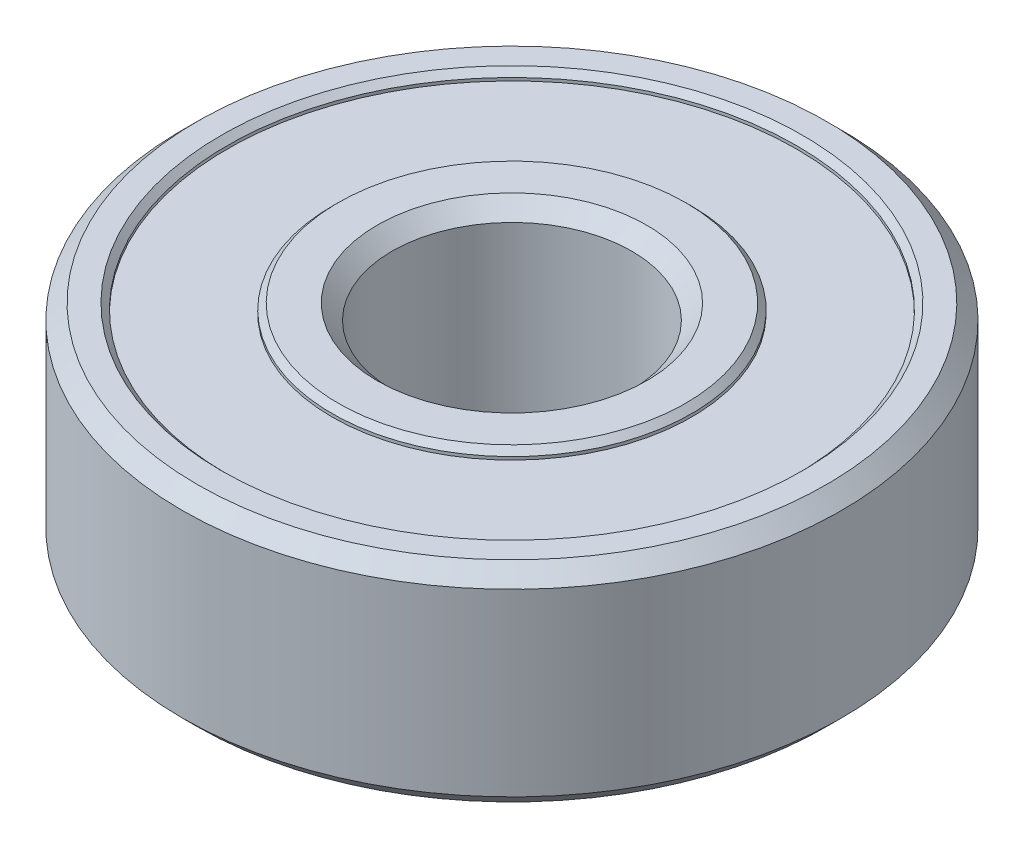
SolidWorks part; units mm, degrees
ref_plane "Front Plane" through (0, 0, 0) normal (0, 0, 1) x (1, 0, 0)
ref_plane "Top Plane" through (0, 0, 0) normal (0, 1, 0) x (1, 0, 0)
ref_plane "Right Plane" through (0, 0, 0) normal (1, 0, 0) x (0, 0, -1)
sketch "Sketch1" plane through (0, 0, 0) normal (0, 1, 0) x (1, 0, 0)
  circle A0 centre (0, 0) radius 11
  circle A1 centre (0, 0) radius 4
  circle A2 centre (0, 0) radius 6
  circle A3 centre (0, 0) radius 9.5
  dimension "D1" = 22
  dimension "D2" = 8
  dimension "D3" = 12
  dimension "D4" = 19
extrude "Boss-Extrude1" add sketch "Sketch1" along normal blind 7 contours A0 A3 | A2 A1
ref_plane "Plane1" through (0, 6.7, 0) normal (0, 1, 0) x (1, 0, 0)
ref_plane "Plane2" through (0, 0.3, 0) normal (0, -1, 0) x (-1, 0, 0)
sketch "Sketch2" plane through (0, 6.7, 0) normal (0, 1, 0) x (1, 0, 0)
  circle A2 centre (0, 0) radius 6
  circle A3 centre (0, 0) radius 6
  circle A5 centre (0, 0) radius 9.5
  circle A6 centre (0, 0) radius 9.5
  dimension "D1" = 0
  dimension "D2" = 0
extrude "Boss-Extrude2" add sketch "Sketch2" against normal up to surface (6.4 mm away) up to plane "Plane2"
chamfer "Chamfer1" distance 0.2 angle 45 4 edges at (0, 0, 6) (0, 0, 9.5) (0, 7, 9.5) (0, 7, 6)
chamfer "Chamfer2" distance 0.5 angle 45 4 edges at (0, 0, 11) (0, 7, 11) (0, 0, 4) (0, 7, 4)
